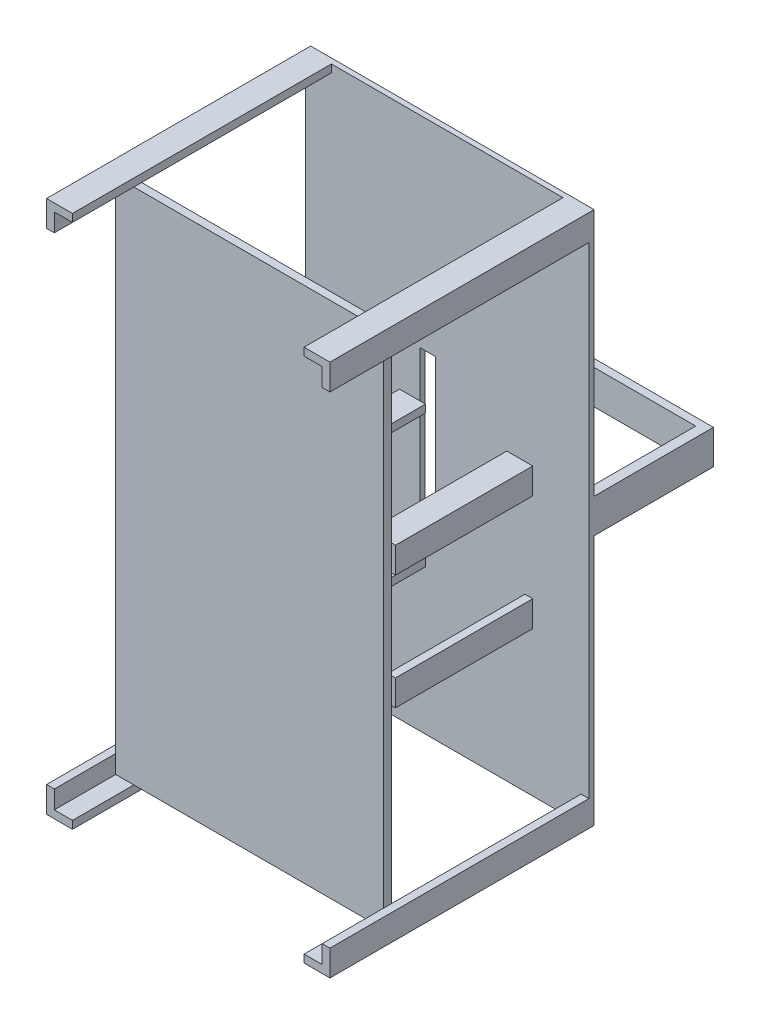
SolidWorks part; units mm, degrees
ref_plane "Front Plane" through (0, 0, 0) normal (0, 0, 1) x (1, 0, 0)
ref_plane "Top Plane" through (0, 0, 0) normal (0, 1, 0) x (1, 0, 0)
ref_plane "Right Plane" through (0, 0, 0) normal (1, 0, 0) x (0, 0, -1)
sketch "Sketch1" plane through (0, 0, 0) normal (0, 0, 1) x (1, 0, 0)
  line L1 (-1397.9334, 1430.0426) -> (102.0666, 1430.0426)
  line L2 (-1397.9334, 1430.0426) -> (-1397.9334, -69.9574)
  line L3 (-1397.9334, -69.9574) -> (102.0666, -69.9574)
  line L4 (102.0666, 1430.0426) -> (102.0666, -69.9574)
  line L5 (-1397.9334, 1430.0426) -> (102.0666, -69.9574) construction
  line L6 (-1397.9334, -69.9574) -> (102.0666, 1430.0426) construction
  point P0 (-647.9334, 680.0426)
  dimension "D1" = 1500
  dimension "D2" = 1500
extrude "Boss-Extrude1" add sketch "Sketch1" along normal blind 20
sketch "Sketch2" plane through (0, 0, 0) normal (0, 0, -1) x (-1, 0, 0)
  line L0 (896.5958, 1002.2373) -> (896.5958, 452.2373)
  line L1 (896.5958, 452.2373) -> (956.5958, 452.2373)
  line L2 (956.5958, 452.2373) -> (956.5958, 1002.2373)
  line L3 (956.5958, 1002.2373) -> (896.5958, 1002.2373)
  dimension "D1" = 550
  dimension "D2" = 60
extrude "Cut-Extrude1" cut sketch "Sketch2" against normal blind 50
sketch "Sketch3" plane through (0, 0, 20) normal (0, 0, 1) x (1, 0, 0)
  line L0 (-1397.9334, 1180.0314) -> (-303.5174, 1180.0314)
  line L1 (-1397.9334, 1430.0426) -> (-1397.9334, -69.9574) construction
  line L2 (-303.5174, 1180.0314) -> (-303.5174, 320.1251)
  line L3 (-303.5174, 320.1251) -> (-1397.9334, 320.1251)
  line L5 (-1397.9334, 1180.0314) -> (-1644.4902, 1252.1913)
  line L6 (-1644.4902, 1252.1913) -> (-1589.8681, 1438.8244)
  line L7 (-1589.8681, 1438.8244) -> (-1070.2171, 1498.7379)
  line L8 (-1070.2171, 1498.7379) -> (264.7423, 1570.8979)
  line L9 (264.7423, 1570.8979) -> (397.0356, 795.1782)
  line L10 (397.0356, 795.1782) -> (1017.2987, -131.007)
  line L11 (1017.2987, -131.007) -> (191.2113, -395.9784)
  line L12 (191.2113, -395.9784) -> (-1019.3443, -263.4927)
  line L13 (-1019.3443, -263.4927) -> (-1938.5744, -209.9368)
  line L14 (-1938.5744, -209.9368) -> (-2007.9451, 196.8281)
  line L15 (-2007.9451, 196.8281) -> (-1397.9334, 320.1251)
extrude "Cut-Extrude2" cut sketch "Sketch3" against normal through all
sketch "Sketch4" plane through (0, 0, 0) normal (0, 0, -1) x (-1, 0, 0)
  line L0 (303.5174, 1180.0314) -> (303.5174, 1780.0314)
  line L1 (303.5174, 1780.0314) -> (1397.9334, 1780.0314)
  line L2 (1397.9334, 1780.0314) -> (1397.9334, 1180.0314)
  line L3 (1397.9334, -279.8749) -> (303.5174, -279.8749)
  line L4 (303.5174, -279.8749) -> (303.5174, 320.1251)
  line L5 (303.5174, 1180.0314) -> (1397.9334, 1180.0314)
  line L6 (303.5174, 320.1251) -> (1397.9334, 320.1251)
  line L7 (1397.9334, 320.1251) -> (1397.9334, -279.8749)
  dimension "D1" = 600
  dimension "D2" = 600
extrude "Boss-Extrude2" add sketch "Sketch4" against normal blind 20
sketch "Sketch5" plane through (0, 0, 20) normal (0, 0, 1) x (1, 0, 0)
  line L0 (-1397.9334, 1780.0314) -> (-1297.9334, 1780.0314)
  line L1 (-1397.9334, 1780.0314) -> (-303.5174, 1780.0314) construction
  line L2 (-1397.9334, 1780.0314) -> (-1397.9334, 1680.0314)
  line L3 (-1397.9334, 1780.0314) -> (-1397.9334, -279.8749) construction
  line L4 (-1397.9334, 1680.0314) -> (-1367.9334, 1680.0314)
  line L5 (-1367.9334, 1680.0314) -> (-1367.9334, 1750.0314)
  line L6 (-1367.9334, 1750.0314) -> (-1297.9334, 1750.0314)
  line L7 (-1297.9334, 1780.0314) -> (-1297.9334, 1750.0314)
  line L8 (-303.5174, 1780.0314) -> (-403.5174, 1780.0314)
  line L9 (-403.5174, 1780.0314) -> (-403.5174, 1750.0314)
  line L10 (-403.5174, 1750.0314) -> (-333.5174, 1750.0314)
  line L11 (-333.5174, 1750.0314) -> (-333.5174, 1680.0314)
  line L12 (-333.5174, 1680.0314) -> (-303.5174, 1680.0314)
  line L13 (-303.5174, 1780.0314) -> (-303.5174, -279.8749) construction
  line L14 (-303.5174, 1680.0314) -> (-303.5174, 1780.0314)
  line L15 (-1397.9334, -179.8749) -> (-1397.9334, -279.8749)
  line L16 (-1397.9334, -279.8749) -> (-1297.9334, -279.8749)
  line L17 (-303.5174, -279.8749) -> (-1397.9334, -279.8749) construction
  line L18 (-1297.9334, -279.8749) -> (-1297.9334, -249.8749)
  line L19 (-1297.9334, -249.8749) -> (-1367.9334, -249.8749)
  line L20 (-1367.9334, -249.8749) -> (-1367.9334, -179.8749)
  line L21 (-1367.9334, -179.8749) -> (-1397.9334, -179.8749)
  line L22 (-303.5174, -279.8749) -> (-303.5174, -179.8749)
  line L23 (-303.5174, -179.8749) -> (-333.5174, -179.8749)
  line L24 (-333.5174, -179.8749) -> (-333.5174, -249.8749)
  line L25 (-333.5174, -249.8749) -> (-403.5174, -249.8749)
  line L26 (-403.5174, -249.8749) -> (-403.5174, -279.8749)
  line L27 (-403.5174, -279.8749) -> (-303.5174, -279.8749)
  dimension "D1" = 100
  dimension "D2" = 100
  dimension "D3" = 30
  dimension "D4" = 30
  dimension "D5" = 100
  dimension "D6" = 100
  dimension "D7" = 30
  dimension "D8" = 30
  dimension "D9" = 30
  dimension "D10" = 30
  dimension "D11" = 100
  dimension "D12" = 100
  dimension "D13" = 100
  dimension "D14" = 100
  dimension "D15" = 30
  dimension "D16" = 30
extrude "Boss-Extrude3" add sketch "Sketch5" along normal blind 1000
sketch "Sketch6" plane through (0, 0, 753) normal (0, 0, 1) x (1, 0, 0)
  line L0 (-1367.9334, 1750.0314) -> (-1367.9334, -249.8749)
  line L1 (-1367.9334, -249.8749) -> (-333.5174, -249.8749)
  line L2 (-333.5174, -249.8749) -> (-333.5174, 1750.0314)
  line L3 (-333.5174, 1750.0314) -> (-1367.9334, 1750.0314)
extrude "Boss-Extrude4" add sketch "Sketch6" along normal blind 30
sketch "Sketch8" plane through (0, 0, 753) normal (0, 0, -1) x (-1, 0, 0)
  line L0 (346.6097, 992.9222) -> (417.4823, 997.0265)
  line L2 (347.4823, 997.0265) -> (801.5328, 997.0265) construction
  line L3 (417.4823, 997.0265) -> (417.4823, 1027.0265)
  line L4 (417.4823, 1027.0265) -> (317.4823, 1027.0265)
  line L5 (317.4823, 1027.0265) -> (317.4823, 927.0265)
  line L6 (317.4823, 927.0265) -> (347.4823, 927.0265)
  line L7 (347.4823, 513.1057) -> (347.4823, 997.0265) construction
  line L8 (347.4823, 927.0265) -> (346.6097, 992.9222)
  line L9 (731.5328, 997.0265) -> (731.5328, 1027.0265)
  line L10 (731.5328, 1027.0265) -> (831.5328, 1027.0265)
  line L11 (831.5328, 1027.0265) -> (831.5328, 927.0265)
  line L12 (831.5328, 927.0265) -> (801.5328, 927.0265)
  line L13 (801.5328, 997.0265) -> (801.5328, 513.1057) construction
  line L14 (801.5328, 997.0265) -> (801.5328, 927.0265)
  line L15 (731.5328, 997.0265) -> (801.5328, 997.0265)
  line L16 (801.5328, 583.1057) -> (831.5328, 583.1057)
  line L17 (831.5328, 583.1057) -> (831.5328, 483.1057)
  line L18 (831.5328, 483.1057) -> (731.5328, 483.1057)
  line L19 (801.5328, 513.1057) -> (731.5328, 513.1057)
  line L20 (801.5328, 513.1057) -> (347.4823, 513.1057) construction
  line L21 (731.5328, 513.1057) -> (731.5328, 483.1057)
  line L22 (801.5328, 513.1057) -> (801.5328, 583.1057)
  line L23 (347.4823, 513.1057) -> (347.4823, 583.1057)
  line L24 (347.4823, 583.1057) -> (317.4823, 583.1057)
  line L25 (317.4823, 583.1057) -> (317.4823, 483.1057)
  line L26 (317.4823, 483.1057) -> (417.4823, 483.1057)
  line L27 (417.4823, 483.1057) -> (417.4823, 513.1057)
  line L28 (417.4823, 513.1057) -> (347.4823, 513.1057)
  dimension "D1" = 30
  dimension "D2" = 30
  dimension "D3" = 30
  dimension "D4" = 30
  dimension "D5" = 30
  dimension "D6" = 30
  dimension "D7" = 30
  dimension "D8" = 30
  dimension "D9" = 100
  dimension "D10" = 100
  dimension "D11" = 100
  dimension "D12" = 100
  dimension "D13" = 100
  dimension "D14" = 100
  dimension "D15" = 100
  dimension "D16" = 100
extrude "Boss-Extrude5" add sketch "Sketch8" along normal blind 530 separate body
sketch "Sketch9" plane through (0, 0, 0) normal (0, 0, -1) x (-1, 0, 0)
  line L0 (303.5174, 821.3471) -> (341.9001, 821.3471)
  line L1 (303.5174, 1780.0314) -> (303.5174, -279.8749) construction
  line L2 (341.9001, 821.3471) -> (341.9001, 689.2417)
  line L3 (341.9001, 689.2417) -> (303.5174, 689.2417)
  line L4 (303.5174, 689.2417) -> (303.5174, 821.3471)
extrude "Boss-Extrude6" add sketch "Sketch9" along normal blind 461
sketch "Sketch10" plane through (0, 0, -461) normal (0, 0, -1) x (-1, 0, 0)
  line L0 (303.5174, 821.3471) -> (896.5958, 821.3471)
  line L1 (896.5958, 1002.2373) -> (896.5958, 452.2373) construction
  line L2 (896.5958, 821.3471) -> (896.5958, 906.386)
  line L3 (896.5958, 906.386) -> (956.5958, 906.386)
  line L4 (956.5958, 452.2373) -> (956.5958, 1002.2373) construction
  line L5 (896.5958, 689.2417) -> (896.5958, 617.2789)
  line L6 (896.5958, 617.2789) -> (956.5958, 617.2789)
  line L7 (956.5958, 617.2789) -> (956.5958, 906.386)
  line L8 (896.5958, 689.2417) -> (303.5174, 689.2417)
  line L9 (303.5174, 689.2417) -> (303.5174, 821.3471)
extrude "Boss-Extrude7" add sketch "Sketch10" against normal blind 30
sketch "Sketch11" plane through (0, 0, -461) normal (0, 0, -1) x (-1, 0, 0)
  circle A0 centre (978.9776, 862.6915) radius 22.3819
  circle A1 centre (978.9776, 663.2233) radius 22.3819
extrude "Boss-Extrude8" add sketch "Sketch11" against normal blind 50 separate body
fillet "Fillet1" radius 20 1 edges at (-1001.3595, 862.6915, -411)
fillet "Fillet2" radius 20 1 edges at (-1001.3595, 663.2233, -411)
